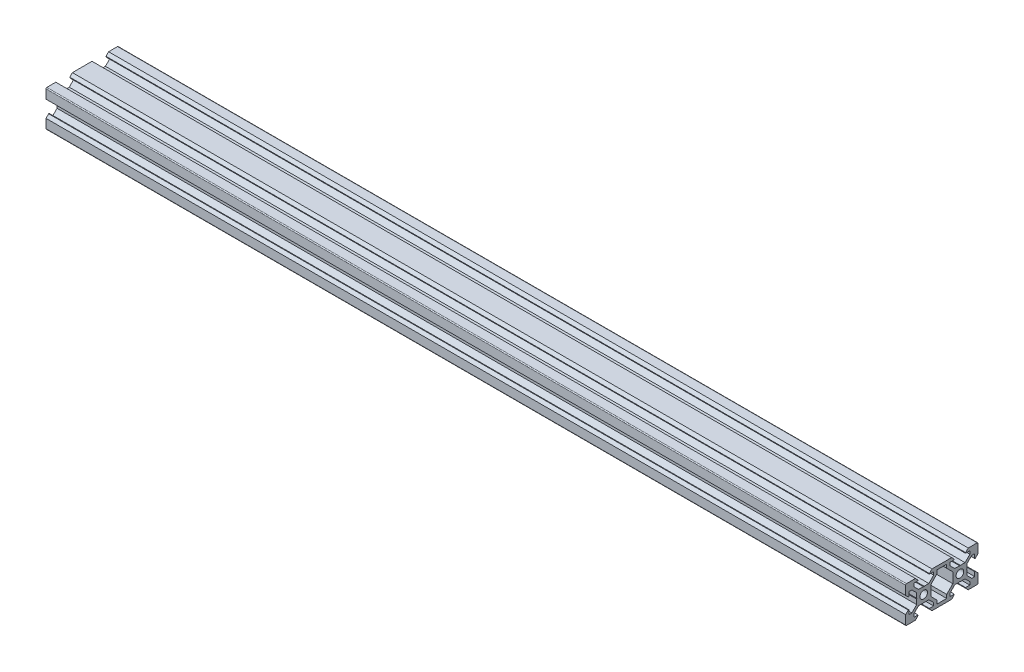
SolidWorks part; units mm, degrees
material "6061-T6 (SS)"
ref_plane "Top" through (0, 0, 0) normal (0, 0, 1) x (1, 0, 0)
ref_plane "Front" through (0, 0, 0) normal (0, 1, 0) x (1, 0, 0)
ref_plane "Right" through (0, 0, 0) normal (1, 0, 0) x (0, 0, -1)
sketch "Profile Sketch" plane through (0, 0, 0) normal (1, 0, 0) x (0, 0, -1)
  line L0 (5.42, 10) -> (-5.42, 10)
  line L1 (-4.5, 8.2) -> (-4.5, 6.56)
  line L2 (-4.5, 6.56) -> (-7.16, 3.9)
  line L3 (-7.16, 3.9) -> (-9.79, 3.9)
  line L4 (-9.79, 3.9) -> (-10, 3.69)
  line L5 (2.7, 8.2) -> (-2.7, 8.2)
  line L6 (-2.7, 8.2) -> (-2.7, 6.2387)
  line L7 (-2.7, 6.2387) -> (-6.1, 2.8387)
  line L8 (-6.1, 2.8387) -> (-6.1, -0.21)
  line L9 (-6.875, 8.545) -> (-6.875, 8.2)
  line L10 (-6.875, 8.2) -> (-4.5, 8.2)
  line L11 (-6.875, 8.545) -> (-5.42, 10)
  line L12 (0, -10) -> (0, 10) construction
  line L13 (-20, 0) -> (20, 0) construction
  line L14 (-10, -10) -> (-10, 10) construction
  line L15 (-6.875, -8.545) -> (-5.42, -10)
  line L16 (-6.875, -8.2) -> (-4.5, -8.2)
  line L17 (-6.875, -8.545) -> (-6.875, -8.2)
  line L18 (-2.7, -6.2387) -> (-6.1, -2.8387)
  line L19 (-2.7, -8.2) -> (-2.7, -6.2387)
  line L20 (2.7, -8.2) -> (-2.7, -8.2)
  line L21 (-7.16, -3.9) -> (-9.79, -3.9)
  line L22 (-4.5, -6.56) -> (-7.16, -3.9)
  line L23 (-4.5, -8.2) -> (-4.5, -6.56)
  line L24 (5.42, -10) -> (-5.42, -10)
  line L25 (-10, 0) -> (-20, 10) construction
  line L26 (-18.545, 3.125) -> (-18.2, 3.125)
  line L27 (-13.125, -8.545) -> (-13.125, -8.2)
  line L28 (-13.125, -8.2) -> (-15.5, -8.2)
  line L29 (-13.125, -8.545) -> (-14.58, -10)
  line L30 (-15.5, -8.2) -> (-15.5, -6.56)
  line L31 (-15.5, -6.56) -> (-12.84, -3.9)
  line L32 (-12.84, -3.9) -> (-10.21, -3.9)
  line L33 (-20, 4.58) -> (-20, 9.5)
  line L34 (-13.9, 2.8387) -> (-13.9, 0.21)
  line L35 (-16.56, 5.5) -> (-13.9, 2.8387)
  line L36 (-12.84, 3.9) -> (-10.21, 3.9)
  line L37 (-15.5, 6.56) -> (-12.84, 3.9)
  line L38 (-15.5, 8.2) -> (-15.5, 6.56)
  line L39 (-13.125, 8.545) -> (-14.58, 10)
  line L40 (-13.125, 8.2) -> (-15.5, 8.2)
  line L41 (-13.125, 8.545) -> (-13.125, 8.2)
  line L42 (-18.2, 3.125) -> (-18.2, 5.5)
  line L43 (-18.545, 3.125) -> (-20, 4.58)
  line L44 (-18.2, 5.5) -> (-16.56, 5.5)
  line L45 (-14.58, 10) -> (-19.5, 10)
  line L46 (-16.56, -5.5) -> (-13.9, -2.8387)
  line L47 (-14.58, -10) -> (-19.5, -10)
  line L48 (-18.2, -5.5) -> (-16.56, -5.5)
  line L49 (-18.545, -3.125) -> (-20, -4.58)
  line L50 (-18.2, -3.125) -> (-18.2, -5.5)
  line L51 (-20, -4.58) -> (-20, -9.5)
  line L52 (-18.545, -3.125) -> (-18.2, -3.125)
  line L53 (10, -10) -> (10, 10) construction
  line L54 (18.545, -3.125) -> (18.2, -3.125)
  line L55 (20, -4.58) -> (20, -9.5)
  line L56 (18.2, -3.125) -> (18.2, -5.5)
  line L57 (18.545, -3.125) -> (20, -4.58)
  line L58 (18.2, -5.5) -> (16.56, -5.5)
  line L59 (14.58, -10) -> (19.5, -10)
  line L60 (16.56, -5.5) -> (13.9, -2.8387)
  line L61 (14.58, 10) -> (19.5, 10)
  line L62 (18.2, 5.5) -> (16.56, 5.5)
  line L63 (18.545, 3.125) -> (20, 4.58)
  line L64 (18.2, 3.125) -> (18.2, 5.5)
  line L65 (13.125, 8.545) -> (13.125, 8.2)
  line L66 (13.125, 8.2) -> (15.5, 8.2)
  line L67 (13.125, 8.545) -> (14.58, 10)
  line L68 (15.5, 8.2) -> (15.5, 6.56)
  line L69 (15.5, 6.56) -> (12.84, 3.9)
  line L70 (12.84, 3.9) -> (10.21, 3.9)
  line L71 (16.56, 5.5) -> (13.9, 2.8387)
  line L72 (13.9, 2.8387) -> (13.9, 0.21)
  line L73 (20, 4.58) -> (20, 9.5)
  line L74 (12.84, -3.9) -> (10.21, -3.9)
  line L75 (15.5, -6.56) -> (12.84, -3.9)
  line L76 (15.5, -8.2) -> (15.5, -6.56)
  line L77 (13.125, -8.545) -> (14.58, -10)
  line L78 (13.125, -8.2) -> (15.5, -8.2)
  line L79 (13.125, -8.545) -> (13.125, -8.2)
  line L80 (18.545, 3.125) -> (18.2, 3.125)
  line L81 (4.5, -8.2) -> (4.5, -6.56)
  line L82 (4.5, -6.56) -> (7.16, -3.9)
  line L83 (7.16, -3.9) -> (9.79, -3.9)
  line L84 (2.7, -8.2) -> (2.7, -6.2387)
  line L85 (2.7, -6.2387) -> (6.1, -2.8387)
  line L86 (6.875, -8.545) -> (6.875, -8.2)
  line L87 (6.875, -8.2) -> (4.5, -8.2)
  line L88 (6.875, -8.545) -> (5.42, -10)
  line L89 (6.875, 8.545) -> (5.42, 10)
  line L90 (6.875, 8.2) -> (4.5, 8.2)
  line L91 (6.875, 8.545) -> (6.875, 8.2)
  line L92 (6.1, 2.8387) -> (6.1, -0.21)
  line L93 (2.7, 6.2387) -> (6.1, 2.8387)
  line L94 (2.7, 8.2) -> (2.7, 6.2387)
  line L95 (9.79, 3.9) -> (10, 3.69)
  line L96 (7.16, 3.9) -> (9.79, 3.9)
  line L97 (4.5, 6.56) -> (7.16, 3.9)
  line L98 (4.5, 8.2) -> (4.5, 6.56)
  line L99 (-10, 3.69) -> (-10.21, 3.9)
  line L100 (-10, -3.69) -> (-10.21, -3.9)
  line L101 (-9.79, -3.9) -> (-10, -3.69)
  line L102 (-13.9, -0.21) -> (-13.69, 0)
  line L103 (-13.69, 0) -> (-13.9, 0.21)
  line L104 (-13.9, -0.21) -> (-13.9, -2.8387)
  line L105 (-6.1, -0.21) -> (-6.31, 0)
  line L106 (-6.31, 0) -> (-6.1, -0.21)
  line L107 (-6.1, -0.21) -> (-6.1, -2.8387)
  line L108 (6.31, 0) -> (6.1, -0.21)
  line L109 (6.1, -0.21) -> (6.31, 0)
  line L110 (13.69, 0) -> (13.9, 0.21)
  line L111 (13.9, -0.21) -> (13.69, 0)
  line L112 (9.79, -3.9) -> (10, -3.69)
  line L113 (10, -3.69) -> (10.21, -3.9)
  line L114 (10, 3.69) -> (10.21, 3.9)
  line L115 (6.1, -0.21) -> (6.1, -2.8387)
  line L116 (13.9, -0.21) -> (13.9, -2.8387)
  line L118 (20, -10) -> (20, 10) construction
  line L119 (20, -10) -> (-20, -10) construction
  line L120 (-20, -10) -> (-20, 10) construction
  line L121 (20, 10) -> (-20, 10) construction
  line L122 (20, -10) -> (-20, 10) construction
  line L123 (-20, -10) -> (20, 10) construction
  circle A0 centre (-10, 0) radius 2.1
  arc A1 (-19.5, 10) -> (-20, 9.5) centre (-19.5, 9.5) ccw
  arc A2 (-19.5, -10) -> (-20, -9.5) centre (-19.5, -9.5) cw
  arc A3 (19.5, -10) -> (20, -9.5) centre (19.5, -9.5) ccw
  arc A4 (19.5, 10) -> (20, 9.5) centre (19.5, 9.5) cw
  circle A5 centre (10, 0) radius 2.1
  point P35 (-2.4957, 0)
  point P108 (0, -8.2)
  point P119 (0, 8.2)
  point P123 (2.4957, 0)
  point P131 (0, 0)
  point P143 (0, 0)
  dimension "D4" = 5.42
  dimension "D5" = 40
  dimension "D6" = 4.2
  dimension "D16" = 0.5
  dimension "D1" = 0.21
  dimension "D2" = 45
  dimension "D3" = 20
  dimension "D7" = 1.5
  dimension "D8" = 1.8
  dimension "D9" = 10
  dimension "D10" = 3.9
  dimension "D11" = 3.9
  dimension "D12" = 1.8
  dimension "D13" = 3.125
  dimension "D14" = 5.5
  dimension "D15" = 1.64
  dimension "D17" = 5.4
extrude "Profile Extrude" add sketch "Profile Sketch" along normal blind 475 contours A4 L61 L67 L65 L66 L68 L69 L70 L114 L95 L96 L97 L98 L90 L91 L89 L0 L11 L9 L10 L1 L2 L3 L4 L99 L36 L37 L38 L40 L41 L39 L45 A1 L33 L43 L26 L42 L44 L35 L34 L103 L102 L104 L46 L48 L50 L52 L49 L51 A2 L47
equation "\"M2x0.4_Close_Hole\"= 2.2"
equation "\"M2.5x0.45_Close_Hole\"= 2.7"
equation "\"M3x0.5_Close_Hole\"= 3.2"
equation "\"M4x0.7_Close_Hole\"= 4.3"
equation "\"M5x0.8_Close_Hole\"= 5.3"
equation "\"M6x1_Close_Hole\"= 6.3"
equation "\"M7x1_Close_Hole\"= 7.4"
equation "\"M8x1.25_Close_Hole\"= 8.4"
equation "\"M2x0.4_Tap_Hole_75\"= 1.6"
equation "\"M3x0.5_Tap_Hole_75\"= 2.5"
equation "\"M4x0.7_Tap_Hole_75\"= 3.3"
equation "\"M5x0.8_Tap_Hole_75\"= 4.2"
equation "\"M6x1_Tap_Hole_75\"= 5"
equation "\"M7x1_Tap_Hole_75\"= 6"
equation "\"M8x1.25_Tap_Hole_75\"= 6.8"
